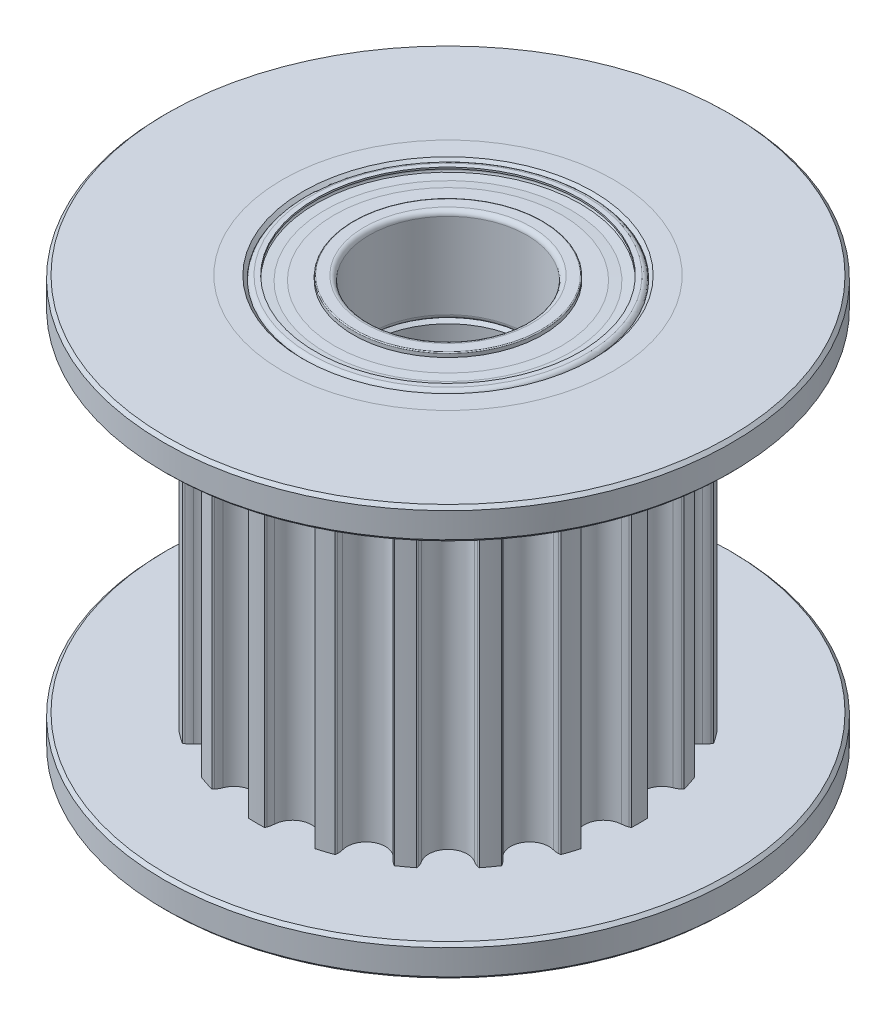
SolidWorks part; units mm, degrees
material "6061-T6 (SS)"
ref_plane "Přední rovina" through (0, 0, 0) normal (0, 0, 1) x (1, 0, 0)
ref_plane "Horní rovina" through (0, 0, 0) normal (0, 1, 0) x (1, 0, 0)
ref_plane "Pravá rovina" through (0, 0, 0) normal (1, 0, 0) x (0, 0, -1)
sketch "Skica1" plane through (0, 0, 0) normal (0, 0, 1) x (1, 0, 0)
  line L0 (4.5, 13) -> (5.25, 13)
  line L1 (5.25, 13) -> (5.25, 12)
  line L2 (5.25, 12) -> (6.075, 12)
  line L3 (6.075, 12) -> (6.075, 1)
  line L4 (6.075, 1) -> (5.25, 1)
  line L5 (5.25, 1) -> (5.25, 0)
  line L6 (5.25, 0) -> (4.5, 0)
  line L8 (4.5, 13) -> (4.5, 10)
  line L9 (4.5, 10) -> (2.5, 10)
  line L10 (2.5, 10) -> (2.5, 3)
  line L11 (2.5, 3) -> (4.5, 3)
  line L12 (4.5, 3) -> (4.5, 0)
  line L13 (0, 0) -> (0, -4.1646) construction
  dimension "D1" = 13
  dimension "D2" = 11
  dimension "D3" = 4.5
  dimension "D4" = 2.5
  dimension "D5" = 6.075
  dimension "D6" = 3
  dimension "D7" = 5.25
revolve "Rotovat1" add sketch "Skica1" angle 360 about L13
chamfer "Zkosení1" distance 0.1 angle 45 4 edges at (0, 3, 2.5) (0, 0, 4.5) (0, 10, 2.5) (0, 13, 4.5)
fillet "Zaoblit1" radius 0.1 2 edges at (0, 3, 4.5) (0, 10, 4.5)
sketch "Skica11" plane through (0, 12, 0) normal (0, 1, 0) x (1, 0, 0)
  line L0 (0, -55) -> (0, 55) construction
  line L1 (-55, 0) -> (55, 0) construction
  point P5 (0, 6.1087)
  arc B0 (-3.6824, -4.5256) -> (-4.5256, -3.6824) centre (-4.1938, -4.1938) ccw
  arc B1 (-3.6824, -4.5256) -> (-3.7624, -4.7003) centre (-3.1284, -4.885) ccw
  arc B2 (-3.7624, -4.7003) -> (-3.7672, -4.8088) centre (-3.5429, -4.7643) ccw
  arc B3 (-3.7672, -4.8088) -> (-3.4093, -5.0688) centre (0, 0) ccw
  arc B4 (-3.4093, -5.0688) -> (-3.3076, -5.0308) centre (-3.4362, -4.8418) ccw
  arc B5 (-3.3076, -5.0308) -> (-3.1662, -4.9006) centre (-3.6792, -4.4848) ccw
  arc B6 (-2.1037, -5.442) -> (-3.1662, -4.9006) centre (-2.6926, -5.2845) ccw
  arc B7 (-2.1037, -5.442) -> (-2.1258, -5.6329) centre (-1.4657, -5.6126) ccw
  arc B8 (-2.1258, -5.6329) -> (-2.0968, -5.7376) centre (-1.8973, -5.6259) ccw
  arc B9 (-2.0968, -5.7376) -> (-1.6761, -5.8742) centre (0, 0) ccw
  arc B10 (-1.6761, -5.8742) -> (-1.5911, -5.8066) centre (-1.7719, -5.6667) ccw
  arc B11 (-1.5911, -5.8066) -> (-1.4968, -5.6392) centre (-2.1132, -5.4022) ccw
  arc B12 (-0.319, -5.8257) -> (-1.4968, -5.6392) centre (-0.9278, -5.8579) ccw
  arc B13 (-0.319, -5.8257) -> (-0.2811, -6.0141) centre (0.3404, -5.7909) ccw
  arc B14 (-0.2811, -6.0141) -> (-0.2211, -6.1047) centre (-0.0659, -5.9369) ccw
  arc B15 (-0.2211, -6.1047) -> (0.2211, -6.1047) centre (0, 0) ccw
  arc B16 (0.2211, -6.1047) -> (0.2811, -6.0141) centre (0.0659, -5.9369) ccw
  arc B17 (0.2811, -6.0141) -> (0.319, -5.8257) centre (-0.3404, -5.7909) ccw
  arc B18 (1.4968, -5.6392) -> (0.319, -5.8257) centre (0.9278, -5.8579) ccw
  arc B19 (1.4968, -5.6392) -> (1.5911, -5.8066) centre (2.1132, -5.4022) ccw
  arc B20 (1.5911, -5.8066) -> (1.6761, -5.8742) centre (1.7719, -5.6667) ccw
  arc B21 (1.6761, -5.8742) -> (2.0968, -5.7376) centre (0, 0) ccw
  arc B22 (2.0968, -5.7376) -> (2.1258, -5.6329) centre (1.8973, -5.6259) ccw
  arc B23 (2.1258, -5.6329) -> (2.1037, -5.442) centre (1.4657, -5.6126) ccw
  arc B24 (3.1662, -4.9006) -> (2.1037, -5.442) centre (2.6926, -5.2845) ccw
  arc B25 (3.1662, -4.9006) -> (3.3076, -5.0308) centre (3.6792, -4.4848) ccw
  arc B26 (3.3076, -5.0308) -> (3.4093, -5.0688) centre (3.4362, -4.8418) ccw
  arc B27 (3.4093, -5.0688) -> (3.7672, -4.8088) centre (0, 0) ccw
  arc B28 (3.7672, -4.8088) -> (3.7624, -4.7003) centre (3.5429, -4.7643) ccw
  arc B29 (3.7624, -4.7003) -> (3.6824, -4.5256) centre (3.1284, -4.885) ccw
  arc B30 (4.5256, -3.6824) -> (3.6824, -4.5256) centre (4.1938, -4.1938) ccw
  arc B31 (4.5256, -3.6824) -> (4.7003, -3.7624) centre (4.885, -3.1284) ccw
  arc B32 (4.7003, -3.7624) -> (4.8088, -3.7672) centre (4.7643, -3.5429) ccw
  arc B33 (4.8088, -3.7672) -> (5.0688, -3.4093) centre (0, 0) ccw
  arc B34 (5.0688, -3.4093) -> (5.0308, -3.3076) centre (4.8418, -3.4362) ccw
  arc B35 (5.0308, -3.3076) -> (4.9006, -3.1662) centre (4.4848, -3.6792) ccw
  arc B36 (5.442, -2.1037) -> (4.9006, -3.1662) centre (5.2845, -2.6926) ccw
  arc B37 (5.442, -2.1037) -> (5.6329, -2.1258) centre (5.6126, -1.4657) ccw
  arc B38 (5.6329, -2.1258) -> (5.7376, -2.0968) centre (5.6259, -1.8973) ccw
  arc B39 (5.7376, -2.0968) -> (5.8742, -1.6761) centre (0, 0) ccw
  arc B40 (5.8742, -1.6761) -> (5.8066, -1.5911) centre (5.6667, -1.7719) ccw
  arc B41 (5.8066, -1.5911) -> (5.6392, -1.4968) centre (5.4022, -2.1132) ccw
  arc B42 (5.8257, -0.319) -> (5.6392, -1.4968) centre (5.8579, -0.9278) ccw
  arc B43 (5.8257, -0.319) -> (6.0141, -0.2811) centre (5.7909, 0.3404) ccw
  arc B44 (6.0141, -0.2811) -> (6.1047, -0.2211) centre (5.9369, -0.0659) ccw
  arc B45 (6.1047, -0.2211) -> (6.1047, 0.2211) centre (0, 0) ccw
  arc B46 (6.1047, 0.2211) -> (6.0141, 0.2811) centre (5.9369, 0.0659) ccw
  arc B47 (6.0141, 0.2811) -> (5.8257, 0.319) centre (5.7909, -0.3404) ccw
  arc B48 (5.6392, 1.4968) -> (5.8257, 0.319) centre (5.8579, 0.9278) ccw
  arc B49 (5.6392, 1.4968) -> (5.8066, 1.5911) centre (5.4022, 2.1132) ccw
  arc B50 (5.8066, 1.5911) -> (5.8742, 1.6761) centre (5.6667, 1.7719) ccw
  arc B51 (5.8742, 1.6761) -> (5.7376, 2.0968) centre (0, 0) ccw
  arc B52 (5.7376, 2.0968) -> (5.6329, 2.1258) centre (5.6259, 1.8973) ccw
  arc B53 (5.6329, 2.1258) -> (5.442, 2.1037) centre (5.6126, 1.4657) ccw
  arc B54 (4.9006, 3.1662) -> (5.442, 2.1037) centre (5.2845, 2.6926) ccw
  arc B55 (4.9006, 3.1662) -> (5.0308, 3.3076) centre (4.4848, 3.6792) ccw
  arc B56 (5.0308, 3.3076) -> (5.0688, 3.4093) centre (4.8418, 3.4362) ccw
  arc B57 (5.0688, 3.4093) -> (4.8088, 3.7672) centre (0, 0) ccw
  arc B58 (4.8088, 3.7672) -> (4.7003, 3.7624) centre (4.7643, 3.5429) ccw
  arc B59 (4.7003, 3.7624) -> (4.5256, 3.6824) centre (4.885, 3.1284) ccw
  arc B60 (3.6824, 4.5256) -> (4.5256, 3.6824) centre (4.1938, 4.1938) ccw
  arc B61 (3.6824, 4.5256) -> (3.7624, 4.7003) centre (3.1284, 4.885) ccw
  arc B62 (3.7624, 4.7003) -> (3.7672, 4.8088) centre (3.5429, 4.7643) ccw
  arc B63 (3.7672, 4.8088) -> (3.4093, 5.0688) centre (0, 0) ccw
  arc B64 (3.4093, 5.0688) -> (3.3076, 5.0308) centre (3.4362, 4.8418) ccw
  arc B65 (3.3076, 5.0308) -> (3.1662, 4.9006) centre (3.6792, 4.4848) ccw
  arc B66 (2.1037, 5.442) -> (3.1662, 4.9006) centre (2.6926, 5.2845) ccw
  arc B67 (2.1037, 5.442) -> (2.1258, 5.6329) centre (1.4657, 5.6126) ccw
  arc B68 (2.1258, 5.6329) -> (2.0968, 5.7376) centre (1.8973, 5.6259) ccw
  arc B69 (2.0968, 5.7376) -> (1.6761, 5.8742) centre (0, 0) ccw
  arc B70 (1.6761, 5.8742) -> (1.5911, 5.8066) centre (1.7719, 5.6667) ccw
  arc B71 (1.5911, 5.8066) -> (1.4968, 5.6392) centre (2.1132, 5.4022) ccw
  arc B72 (0.319, 5.8257) -> (1.4968, 5.6392) centre (0.9278, 5.8579) ccw
  arc B73 (0.319, 5.8257) -> (0.2811, 6.0141) centre (-0.3404, 5.7909) ccw
  arc B74 (0.2811, 6.0141) -> (0.2211, 6.1047) centre (0.0659, 5.9369) ccw
  arc B75 (0.2211, 6.1047) -> (-0.2211, 6.1047) centre (0, 0) ccw
  arc B76 (-0.2211, 6.1047) -> (-0.2811, 6.0141) centre (-0.0659, 5.9369) ccw
  arc B77 (-0.2811, 6.0141) -> (-0.319, 5.8257) centre (0.3404, 5.7909) ccw
  arc B78 (-1.4968, 5.6392) -> (-0.319, 5.8257) centre (-0.9278, 5.8579) ccw
  arc B79 (-1.4968, 5.6392) -> (-1.5911, 5.8066) centre (-2.1132, 5.4022) ccw
  arc B80 (-1.5911, 5.8066) -> (-1.6761, 5.8742) centre (-1.7719, 5.6667) ccw
  arc B81 (-1.6761, 5.8742) -> (-2.0968, 5.7376) centre (0, 0) ccw
  arc B82 (-2.0968, 5.7376) -> (-2.1258, 5.6329) centre (-1.8973, 5.6259) ccw
  arc B83 (-2.1258, 5.6329) -> (-2.1037, 5.442) centre (-1.4657, 5.6126) ccw
  arc B84 (-3.1662, 4.9006) -> (-2.1037, 5.442) centre (-2.6926, 5.2845) ccw
  arc B85 (-3.1662, 4.9006) -> (-3.3076, 5.0308) centre (-3.6792, 4.4848) ccw
  arc B86 (-3.3076, 5.0308) -> (-3.4093, 5.0688) centre (-3.4362, 4.8418) ccw
  arc B87 (-3.4093, 5.0688) -> (-3.7672, 4.8088) centre (0, 0) ccw
  arc B88 (-3.7672, 4.8088) -> (-3.7624, 4.7003) centre (-3.5429, 4.7643) ccw
  arc B89 (-3.7624, 4.7003) -> (-3.6824, 4.5256) centre (-3.1284, 4.885) ccw
  arc B90 (-4.5256, 3.6824) -> (-3.6824, 4.5256) centre (-4.1938, 4.1938) ccw
  arc B91 (-4.5256, 3.6824) -> (-4.7003, 3.7624) centre (-4.885, 3.1284) ccw
  arc B92 (-4.7003, 3.7624) -> (-4.8088, 3.7672) centre (-4.7643, 3.5429) ccw
  arc B93 (-4.8088, 3.7672) -> (-5.0688, 3.4093) centre (0, 0) ccw
  arc B94 (-5.0688, 3.4093) -> (-5.0308, 3.3076) centre (-4.8418, 3.4362) ccw
  arc B95 (-5.0308, 3.3076) -> (-4.9006, 3.1662) centre (-4.4848, 3.6792) ccw
  arc B96 (-5.442, 2.1037) -> (-4.9006, 3.1662) centre (-5.2845, 2.6926) ccw
  arc B97 (-5.442, 2.1037) -> (-5.6329, 2.1258) centre (-5.6126, 1.4657) ccw
  arc B98 (-5.6329, 2.1258) -> (-5.7376, 2.0968) centre (-5.6259, 1.8973) ccw
  arc B99 (-5.7376, 2.0968) -> (-5.8742, 1.6761) centre (0, 0) ccw
  arc B100 (-5.8742, 1.6761) -> (-5.8066, 1.5911) centre (-5.6667, 1.7719) ccw
  arc B101 (-5.8066, 1.5911) -> (-5.6392, 1.4968) centre (-5.4022, 2.1132) ccw
  arc B102 (-5.8257, 0.319) -> (-5.6392, 1.4968) centre (-5.8579, 0.9278) ccw
  arc B103 (-5.8257, 0.319) -> (-6.0141, 0.2811) centre (-5.7909, -0.3404) ccw
  arc B104 (-6.0141, 0.2811) -> (-6.1047, 0.2211) centre (-5.9369, 0.0659) ccw
  arc B105 (-6.1047, 0.2211) -> (-6.1047, -0.2211) centre (0, 0) ccw
  arc B106 (-6.1047, -0.2211) -> (-6.0141, -0.2811) centre (-5.9369, -0.0659) ccw
  arc B107 (-6.0141, -0.2811) -> (-5.8257, -0.319) centre (-5.7909, 0.3404) ccw
  arc B108 (-5.6392, -1.4968) -> (-5.8257, -0.319) centre (-5.8579, -0.9278) ccw
  arc B109 (-5.6392, -1.4968) -> (-5.8066, -1.5911) centre (-5.4022, -2.1132) ccw
  arc B110 (-5.8066, -1.5911) -> (-5.8742, -1.6761) centre (-5.6667, -1.7719) ccw
  arc B111 (-5.8742, -1.6761) -> (-5.7376, -2.0968) centre (0, 0) ccw
  arc B112 (-5.7376, -2.0968) -> (-5.6329, -2.1258) centre (-5.6259, -1.8973) ccw
  arc B113 (-5.6329, -2.1258) -> (-5.442, -2.1037) centre (-5.6126, -1.4657) ccw
  arc B114 (-4.9006, -3.1662) -> (-5.442, -2.1037) centre (-5.2845, -2.6926) ccw
  arc B115 (-4.9006, -3.1662) -> (-5.0308, -3.3076) centre (-4.4848, -3.6792) ccw
  arc B116 (-5.0308, -3.3076) -> (-5.0688, -3.4093) centre (-4.8418, -3.4362) ccw
  arc B117 (-5.0688, -3.4093) -> (-4.8088, -3.7672) centre (0, 0) ccw
  arc B118 (-4.8088, -3.7672) -> (-4.7003, -3.7624) centre (-4.7643, -3.5429) ccw
  arc B119 (-4.7003, -3.7624) -> (-4.5256, -3.6824) centre (-4.885, -3.1284) ccw
sketch_block_instance "Blok1-1"
sketch_block "Blok1"
extrude "Odebrat vysunutím1" cut sketch "Skica11" against normal through all flip side to cut
sketch "Skica10" plane through (0, 13, 0) normal (0, 1, 0) x (1, 0, 0)
  circle A0 centre (0, 0) radius 9
  circle A1 centre (0, 0) radius 5.25 construction
  circle A2 centre (0, 0) radius 5.25
  dimension "D1" = 18
extrude "Přidat vysunutím1" add sketch "Skica10" against normal up to surface (1 mm away) separate body up to face at (0, 12, 5.25)
sketch "Skica12" plane through (0, 0, 0) normal (0, -1, 0) x (1, 0, 0)
  circle A0 centre (0, 0) radius 9
  circle A1 centre (0, 0) radius 5.25 construction
  circle A2 centre (0, 0) radius 5.25
  circle A3 centre (0, 0) radius 9 construction
extrude "Přidat vysunutím2" add sketch "Skica12" against normal up to surface (1 mm away) separate body up to face at (0, 1, 5.25)
chamfer "Zkosení2" distance 0.1 angle 45 2 edges at (0, 12, -9) (0, 13, 9)
chamfer "Zkosení3" distance 0.1 angle 45 2 edges at (0, 0, -9) (0, 1, 9)
sketch "Skica4" plane through (0, 0, 0) normal (0, 0, 1) x (1, 0, 0)
  line L0 (4.5, 12.85) -> (4.5, 10.15)
  line L1 (4.35, 10) -> (4.2, 10)
  line L2 (4.2, 10) -> (4.2, 10.05)
  line L3 (3.85, 10.2828) -> (4.2132, 10.229)
  line L4 (3.85, 10.2828) -> (3.85, 11.0528)
  line L5 (3.85, 11.9472) -> (3.85, 12.7172)
  line L6 (3.85, 12.7172) -> (4.2132, 12.771)
  line L7 (4.35, 13) -> (4.2, 13)
  line L8 (4.2, 13) -> (4.2, 12.95)
  line L9 (0, 0) -> (0, 18.4294) construction
  line L10 (4.4, 10) -> (-4.4, 10) construction
  arc A0 (4.35, 13) -> (4.5, 12.85) centre (4.35, 12.85) cw
  arc A1 (4.35, 10) -> (4.5, 10.15) centre (4.35, 10.15) ccw
  arc A2 (4.2, 12.95) -> (4.2132, 12.771) centre (4.2, 12.86) cw
  arc A3 (3.85, 11.9472) -> (3.85, 11.0528) centre (3.45, 11.5) cw
  arc A4 (4.2, 10.05) -> (4.2132, 10.229) centre (4.2, 10.14) ccw
  point P26 (4.5, 11.5)
  point P29 (4.275, 10)
  dimension "D3" = 0.09
  dimension "D6" = 0.15
  dimension "D7" = 0.6
  dimension "D1" = 4.5
  dimension "D2" = 3.85
  dimension "D4" = 0.05
  dimension "D5" = 0.15
  dimension "D8" = 0.77
  dimension "D9" = 3
  dimension "D10" = 1.05
revolve "Rotovat2" add sketch "Skica4" angle 360 about L9
sketch "Skica5" plane through (0, 0, 0) normal (0, 0, 1) x (1, 0, 0)
  line L0 (2.5, 12.85) -> (2.5, 10.15)
  line L1 (2.65, 13) -> (2.97, 13)
  line L2 (3, 12.97) -> (3, 12.86)
  line L3 (3, 12.86) -> (3.6, 12.86)
  line L4 (3.6, 12.86) -> (3.9, 12.84)
  line L5 (3.9, 12.84) -> (4.2, 12.86)
  line L6 (4.2, 12.86) -> (4.2, 12.81)
  line L7 (4.2, 12.81) -> (3.9, 12.77)
  line L8 (3.9, 12.77) -> (3.6, 12.77)
  line L9 (3.6, 12.77) -> (3, 12.81)
  line L10 (3, 12.81) -> (3, 11.8969)
  line L11 (2.65, 10) -> (2.97, 10)
  line L12 (0, 0) -> (0, 20.363) construction
  line L13 (3, 10.03) -> (3, 10.14)
  line L21 (3, 10.19) -> (3, 11.1031)
  line L22 (3, 10.14) -> (3.6, 10.14)
  line L23 (3.6, 10.14) -> (3.8962, 10.1917)
  line L24 (3.8962, 10.1917) -> (4.1924, 10.14)
  line L25 (4.1924, 10.14) -> (4.1924, 10.19)
  line L26 (4.1924, 10.19) -> (3.8975, 10.2581)
  line L27 (3.8975, 10.2581) -> (3.5975, 10.2581)
  line L28 (3.5975, 10.2581) -> (3, 10.19)
  line L29 (-4.2, 10) -> (4.2, 10) construction
  arc A0 (2.65, 10) -> (2.5, 10.15) centre (2.65, 10.15) cw
  arc A1 (2.65, 13) -> (2.5, 12.85) centre (2.65, 12.85) ccw
  arc A2 (3, 12.97) -> (2.97, 13) centre (2.97, 12.97) ccw
  arc A3 (3, 10.03) -> (2.97, 10) centre (2.97, 10.03) cw
  arc A4 (3, 11.8969) -> (3, 11.1031) centre (3.45, 11.5) ccw
  dimension "D3" = 0.15
  dimension "D4" = 0.11
  dimension "D5" = 0.03
  dimension "D7" = 0.6
  dimension "D1" = 2.5
  dimension "D2" = 3
  dimension "D6" = 0.6
  dimension "D8" = 0.95
  dimension "D9" = 3
  dimension "D10" = 1.2
  dimension "D11" = 0.3
  dimension "D12" = 0.05
  dimension "D13" = 0.9
  dimension "D14" = 0.6
  dimension "D15" = 0.09
  dimension "D16" = 0.05
  dimension "D17" = 0.05
revolve "Rotovat3" add sketch "Skica5" angle 360 about L12
sketch "Skica6" plane through (0, 0, 0) normal (0, 0, 1) x (1, 0, 0)
  line L0 (3.45, 12.1) -> (3.45, 10.9)
  line L4 (-4.2, 10) -> (4.2, 10) construction
  arc A0 (3.45, 12.1) -> (3.45, 10.9) centre (3.45, 11.5) cw
  dimension "D1" = 0.6
  dimension "D2" = 1.5
  dimension "D3" = 3.45
revolve "Rotovat4" add sketch "Skica6" angle 360 about L0
pattern_circular "Kruhové pole1" count 8 over 360 about axis through (0, 0, 0) along (0, 1, 0) of bodies 105
sketch "Skica7" plane through (0, 0, 0) normal (0, 0, 1) x (1, 0, 0)
  line L0 (4.5, 2.85) -> (4.5, 0.15)
  line L1 (4.35, 0) -> (4.2, 0)
  line L2 (4.2, 0) -> (4.2, 0.05)
  line L3 (3.85, 0.2828) -> (4.2132, 0.229)
  line L4 (3.85, 0.2828) -> (3.85, 1.0528)
  line L5 (3.85, 1.9472) -> (3.85, 2.7172)
  line L6 (3.85, 2.7172) -> (4.2132, 2.771)
  line L7 (4.35, 3) -> (4.2, 3)
  line L8 (4.2, 3) -> (4.2, 2.95)
  line L9 (0, 0) -> (0, 11.2374) construction
  arc A0 (4.35, 3) -> (4.5, 2.85) centre (4.35, 2.85) cw
  arc A1 (4.35, 0) -> (4.5, 0.15) centre (4.35, 0.15) ccw
  arc A2 (4.2, 2.95) -> (4.2132, 2.771) centre (4.2, 2.86) cw
  arc A3 (3.85, 1.9472) -> (3.85, 1.0528) centre (3.45, 1.5) cw
  arc A4 (4.2, 0.05) -> (4.2132, 0.229) centre (4.2, 0.14) ccw
  point P19 (4.5, 1.5)
  point P20 (4.275, 0)
  dimension "D1" = 0.09
  dimension "D4" = 0.15
  dimension "D5" = 0.6
  dimension "D2" = 0.05
  dimension "D3" = 0.15
  dimension "D6" = 0.77
  dimension "D7" = 3
  dimension "D8" = 1.05
  dimension "D9" = 4.5
  dimension "D10" = 3.85
revolve "Rotovat5" add sketch "Skica7" angle 360 about L9
sketch "Skica8" plane through (0, 0, 0) normal (0, 0, 1) x (1, 0, 0)
  line L0 (2.5, 2.85) -> (2.5, 0.15)
  line L1 (2.65, 3) -> (2.97, 3)
  line L2 (3, 2.97) -> (3, 2.86)
  line L3 (3, 2.86) -> (3.6, 2.86)
  line L4 (3.6, 2.86) -> (3.9, 2.84)
  line L5 (3.9, 2.84) -> (4.2, 2.86)
  line L6 (4.2, 2.86) -> (4.2, 2.81)
  line L7 (4.2, 2.81) -> (3.9, 2.77)
  line L8 (3.9, 2.77) -> (3.6, 2.77)
  line L9 (3.6, 2.77) -> (3, 2.81)
  line L10 (3, 2.81) -> (3, 1.8969)
  line L11 (2.65, 0) -> (2.97, 0)
  line L12 (3, 0.03) -> (3, 0.14)
  line L13 (3, 0.19) -> (3, 1.1031)
  line L14 (3, 0.14) -> (3.6, 0.14)
  line L15 (3.6, 0.14) -> (3.8962, 0.1917)
  line L16 (3.8962, 0.1917) -> (4.1924, 0.14)
  line L17 (4.1924, 0.14) -> (4.1924, 0.19)
  line L18 (4.1924, 0.19) -> (3.8975, 0.2581)
  line L19 (3.8975, 0.2581) -> (3.5975, 0.2581)
  line L20 (3.5975, 0.2581) -> (3, 0.19)
  line L21 (0, 0) -> (0, -2.9362) construction
  arc A0 (2.65, 0) -> (2.5, 0.15) centre (2.65, 0.15) cw
  arc A1 (2.65, 3) -> (2.5, 2.85) centre (2.65, 2.85) ccw
  arc A2 (3, 2.97) -> (2.97, 3) centre (2.97, 2.97) ccw
  arc A3 (3, 0.03) -> (2.97, 0) centre (2.97, 0.03) cw
  arc A4 (3, 1.8969) -> (3, 1.1031) centre (3.45, 1.5) ccw
  dimension "D1" = 0.15
  dimension "D2" = 0.03
  dimension "D5" = 0.6
  dimension "D3" = 0.11
  dimension "D4" = 0.6
  dimension "D6" = 0.95
  dimension "D7" = 3
  dimension "D8" = 1.2
  dimension "D9" = 0.3
  dimension "D10" = 0.05
  dimension "D11" = 0.9
  dimension "D12" = 0.6
  dimension "D13" = 0.09
  dimension "D14" = 0.05
  dimension "D15" = 0.05
  dimension "D16" = 2.5
  dimension "D17" = 3
revolve "Rotovat6" add sketch "Skica8" angle 360 about L21
sketch "Skica9" plane through (0, 0, 0) normal (0, 0, 1) x (1, 0, 0)
  line L0 (3.45, 2.1) -> (3.45, 0.9)
  line L1 (0, -2.351) -> (0, 5.6956) construction
  arc A0 (3.45, 2.1) -> (3.45, 0.9) centre (3.45, 1.5) cw
  dimension "D1" = 0.6
  dimension "D2" = 3.45
  dimension "D3" = 1.5
revolve "Rotovat7" add sketch "Skica9" angle 360 about L0
pattern_circular "Kruhové pole3" count 8 over 360 about axis through (0, 0, 0) along (0, 1, 0) of bodies 123
